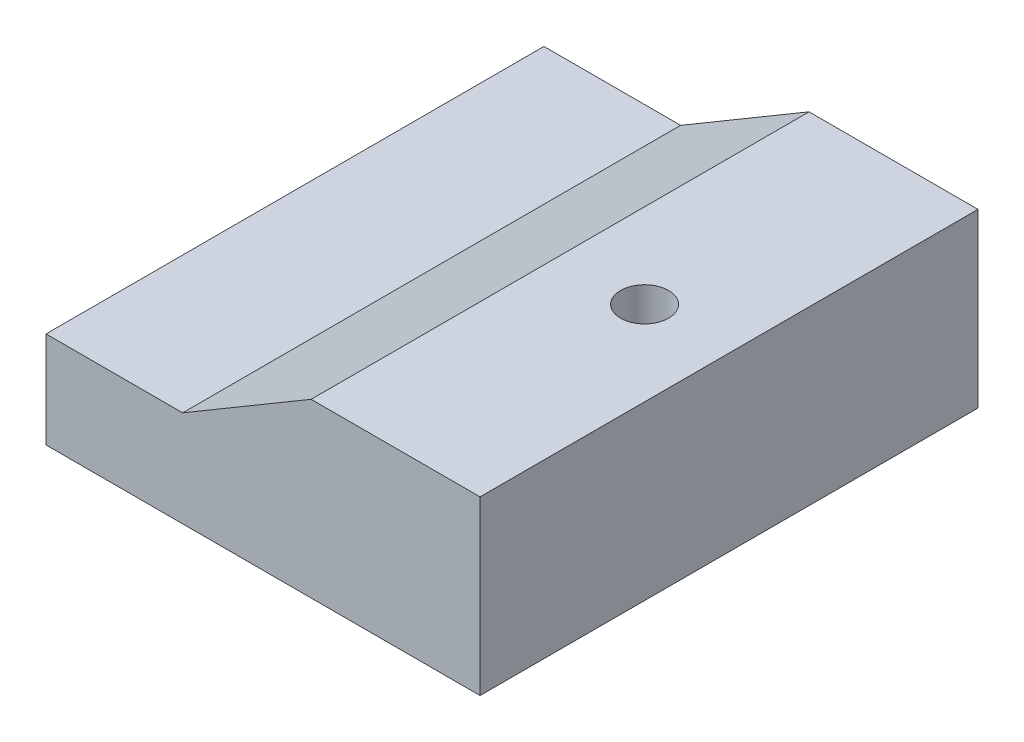
SolidWorks part; units mm, degrees
ref_plane "Front Plane" through (0, 0, 0) normal (0, 0, 1) x (1, 0, 0)
ref_plane "Top Plane" through (0, 0, 0) normal (0, 1, 0) x (1, 0, 0)
ref_plane "Right Plane" through (0, 0, 0) normal (1, 0, 0) x (0, 0, -1)
sketch "Sketch1" plane through (0, 0, 0) normal (0, 0, 1) x (1, 0, 0)
  line L0 (0, 0) -> (-6860, 0)
  line L1 (-6860, 0) -> (-6860, 1520)
  line L2 (-6860, 1520) -> (-4700, 1520)
  line L3 (-4700, 1520) -> (-2670, 2720)
  line L4 (-2670, 2720) -> (0, 2720)
  line L5 (0, 2720) -> (0, 0)
  dimension "D1" = 6860
  dimension "D2" = 2720
  dimension "D3" = 1520
  dimension "D4" = 2160
  dimension "D5" = 2670
extrude "Boss-Extrude1" add sketch "Sketch1" along normal blind 7870
sketch "Sketch2" plane through (0, 2720, 0) normal (0, 1, 0) x (1, 0, 0)
  line L0 (0, -3935) -> (-2670, -3935) construction
  line L1 (0, -7870) -> (0, 0) construction
  line L2 (-2670, -7870) -> (-2670, 0) construction
  circle A0 centre (-1335, -3935) radius 380
  dimension "D1" = 760
extrude "Cut-Extrude1" cut sketch "Sketch2" against normal through all
